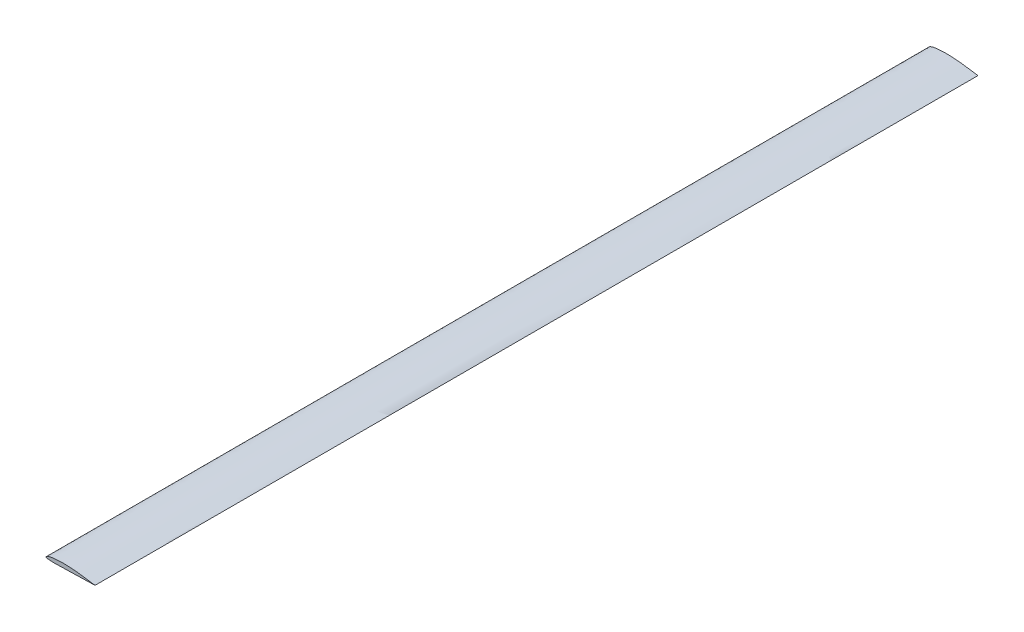
SolidWorks part; units mm, degrees
material "1060 Alloy"
ref_plane "Front Plane" through (0, 0, 0) normal (0, 0, 1) x (1, 0, 0)
ref_plane "Top Plane" through (0, 0, 0) normal (0, 1, 0) x (1, 0, 0)
ref_plane "Right Plane" through (0, 0, 0) normal (1, 0, 0) x (0, 0, -1)
curve "Curve1"
  spline degree 3 poles (99.303, 0.018, 0) (100.1768, -0.0106, 0) (99.3044, 0.0659, 0) (98.6022, 0.1664, 0) (96.9185, 0.3889, 0) (94.883, 0.6998, 0) (92.2676, 1.1097, 0) (89.231, 1.5986, 0) (85.7846, 2.1502, 0) (81.9915, 2.742, 0) (77.8954, 3.3493, 0) (73.5406, 3.9422, 0) (68.9677, 4.4995, 0) (64.218, 5.0097, 0) (59.3372, 5.4645, 0) (54.3778, 5.8636, 0) (49.3943, 6.1992, 0) (44.4376, 6.4503, 0) (39.5569, 6.6096, 0) (34.7991, 6.6775, 0) (30.2086, 6.6419, 0) (25.8275, 6.4985, 0) (21.6951, 6.2592, 0) (17.849, 5.9192, 0) (14.3226, 5.4809, 0) (11.143, 4.9534, 0) (8.3342, 4.3478, 0) (5.9153, 3.6753, 0) (3.9009, 2.9545, 0) (2.2976, 2.2061, 0) (1.1175, 1.4622, 0) (0.4562, 0.8732, 0) (0.18, 0.4789, 0) (0.0816, 0.3044, 0) (0.0209, 0.1477, 0) (-0.0031, 0.0241, 0) (0.0017, -0.0733, 0) (0.0494, -0.1608, 0) (0.1388, -0.2609, 0) (0.2821, -0.3771, 0) (0.6288, -0.5925, 0) (1.401, -0.9072, 0) (2.7562, -1.2563, 0) (4.6749, -1.5755, 0) (7.0779, -1.8364, 0) (9.9483, -2.0308, 0) (13.2624, -2.1587, 0) (16.9912, -2.2213, 0) (21.0993, -2.224, 0) (25.5455, -2.1736, 0) (30.2829, -2.0779, 0) (35.2597, -1.9445, 0) (40.4207, -1.7811, 0) (45.7076, -1.5953, 0) (51.0606, -1.3938, 0) (56.4181, -1.185, 0) (61.7181, -0.9753, 0) (66.898, -0.7732, 0) (71.8957, -0.5848, 0) (76.65, -0.4161, 0) (81.102, -0.2717, 0) (85.1928, -0.157, 0) (88.8721, -0.0729, 0) (92.0755, -0.0183, 0) (94.798, 0.0086, 0) (96.8881, 0.0191, 0) (98.5945, 0.0084, 0) (99.303, 0.018, 0) (100.1768, -0.0106, 0) (99.3044, 0.0659, 0) knots -0.014204 -0.006419 -0.001632 0 0.001631 0.006435 0.014221 0.024766 0.037827 0.053149 0.070474 0.089536 0.110075 0.13186 0.154693 0.178371 0.20268 0.227364 0.252133 0.276728 0.300939 0.324527 0.347267 0.368992 0.389507 0.408628 0.426224 0.442179 0.456396 0.468805 0.479372 0.488086 0.494968 0.500034 0.501036 0.502094 0.502997 0.503513 0.503956 0.504409 0.504955 0.505943 0.50713 0.510998 0.518232 0.527846 0.539809 0.554056 0.57049 0.588974 0.609342 0.631393 0.654894 0.67959 0.705203 0.731447 0.75802 0.78462 0.810936 0.836657 0.861473 0.885081 0.907188 0.927507 0.945765 0.961712 0.975122 0.985796 0.993581 0.998368 1 1.001631 1.006435 1.014221 periodic
sketch "Sketch1" plane through (0, 0, 0) normal (0, 0, 1) x (1, 0, 0)
  spline S0 degree 3 poles (99.303, 0.018) (100.1768, -0.0106) (99.3044, 0.0659) (98.6022, 0.1664) (96.9185, 0.3889) (94.883, 0.6998) (92.2676, 1.1097) (89.231, 1.5986) (85.7846, 2.1502) (81.9915, 2.742) (77.8954, 3.3493) (73.5406, 3.9422) (68.9677, 4.4995) (64.218, 5.0097) (59.3372, 5.4645) (54.3778, 5.8636) (49.3943, 6.1992) (44.4376, 6.4503) (39.5569, 6.6096) (34.7991, 6.6775) (30.2086, 6.6419) (25.8275, 6.4985) (21.6951, 6.2592) (17.849, 5.9192) (14.3226, 5.4809) (11.143, 4.9534) (8.3342, 4.3478) (5.9153, 3.6753) (3.9009, 2.9545) (2.2976, 2.2061) (1.1175, 1.4622) (0.4562, 0.8732) (0.18, 0.4789) (0.0816, 0.3044) (0.0209, 0.1477) (-0.0031, 0.0241) (0.0017, -0.0733) (0.0494, -0.1608) (0.1388, -0.2609) (0.2821, -0.3771) (0.6288, -0.5925) (1.401, -0.9072) (2.7562, -1.2563) (4.6749, -1.5755) (7.0779, -1.8364) (9.9483, -2.0308) (13.2624, -2.1587) (16.9912, -2.2213) (21.0993, -2.224) (25.5455, -2.1736) (30.2829, -2.0779) (35.2597, -1.9445) (40.4207, -1.7811) (45.7076, -1.5953) (51.0606, -1.3938) (56.4181, -1.185) (61.7181, -0.9753) (66.898, -0.7732) (71.8957, -0.5848) (76.65, -0.4161) (81.102, -0.2717) (85.1928, -0.157) (88.8721, -0.0729) (92.0755, -0.0183) (94.798, 0.0086) (96.8881, 0.0191) (98.5945, 0.0084) (99.303, 0.018) (100.1768, -0.0106) (99.3044, 0.0659) knots -0.014204 -0.006419 -0.001632 0 0.001631 0.006435 0.014221 0.024766 0.037827 0.053149 0.070474 0.089536 0.110075 0.13186 0.154693 0.178371 0.20268 0.227364 0.252133 0.276728 0.300939 0.324527 0.347267 0.368992 0.389507 0.408628 0.426224 0.442179 0.456396 0.468805 0.479372 0.488086 0.494968 0.500034 0.501036 0.502094 0.502997 0.503513 0.503956 0.504409 0.504955 0.505943 0.50713 0.510998 0.518232 0.527846 0.539809 0.554056 0.57049 0.588974 0.609342 0.631393 0.654894 0.67959 0.705203 0.731447 0.75802 0.78462 0.810936 0.836657 0.861473 0.885081 0.907188 0.927507 0.945765 0.961712 0.975122 0.985796 0.993581 0.998368 1 1.001631 1.006435 1.014221 only from (100, 0) to (100, 0) construction
  spline S1 degree 3 poles (99.303, 0.018) (100.1768, -0.0106) (99.3044, 0.0659) (98.6022, 0.1664) (96.9185, 0.3889) (94.883, 0.6998) (92.2676, 1.1097) (89.231, 1.5986) (85.7846, 2.1502) (81.9915, 2.742) (77.8954, 3.3493) (73.5406, 3.9422) (68.9677, 4.4995) (64.218, 5.0097) (59.3372, 5.4645) (54.3778, 5.8636) (49.3943, 6.1992) (44.4376, 6.4503) (39.5569, 6.6096) (34.7991, 6.6775) (30.2086, 6.6419) (25.8275, 6.4985) (21.6951, 6.2592) (17.849, 5.9192) (14.3226, 5.4809) (11.143, 4.9534) (8.3342, 4.3478) (5.9153, 3.6753) (3.9009, 2.9545) (2.2976, 2.2061) (1.1175, 1.4622) (0.4562, 0.8732) (0.18, 0.4789) (0.0816, 0.3044) (0.0209, 0.1477) (-0.0031, 0.0241) (0.0017, -0.0733) (0.0494, -0.1608) (0.1388, -0.2609) (0.2821, -0.3771) (0.6288, -0.5925) (1.401, -0.9072) (2.7562, -1.2563) (4.6749, -1.5755) (7.0779, -1.8364) (9.9483, -2.0308) (13.2624, -2.1587) (16.9912, -2.2213) (21.0993, -2.224) (25.5455, -2.1736) (30.2829, -2.0779) (35.2597, -1.9445) (40.4207, -1.7811) (45.7076, -1.5953) (51.0606, -1.3938) (56.4181, -1.185) (61.7181, -0.9753) (66.898, -0.7732) (71.8957, -0.5848) (76.65, -0.4161) (81.102, -0.2717) (85.1928, -0.157) (88.8721, -0.0729) (92.0755, -0.0183) (94.798, 0.0086) (96.8881, 0.0191) (98.5945, 0.0084) (99.303, 0.018) (100.1768, -0.0106) (99.3044, 0.0659) knots -0.014204 -0.006419 -0.001632 0 0.001631 0.006435 0.014221 0.024766 0.037827 0.053149 0.070474 0.089536 0.110075 0.13186 0.154693 0.178371 0.20268 0.227364 0.252133 0.276728 0.300939 0.324527 0.347267 0.368992 0.389507 0.408628 0.426224 0.442179 0.456396 0.468805 0.479372 0.488086 0.494968 0.500034 0.501036 0.502094 0.502997 0.503513 0.503956 0.504409 0.504955 0.505943 0.50713 0.510998 0.518232 0.527846 0.539809 0.554056 0.57049 0.588974 0.609342 0.631393 0.654894 0.67959 0.705203 0.731447 0.75802 0.78462 0.810936 0.836657 0.861473 0.885081 0.907188 0.927507 0.945765 0.961712 0.975122 0.985796 0.993581 0.998368 1 1.001631 1.006435 1.014221 only from (100, 0) to (100, 0)
extrude "Boss-Extrude1" add sketch "Sketch1" along normal blind 1800
ref_plane "Plane1" through (0, 0, 0) normal (0, 1, 0) x (1, 0, 0)
sketch "Sketch2" plane through (0, 0, 0) normal (0, 1, 0) x (1, 0, 0)
  line L0 (49.9999, -1800) -> (49.9999, 0) construction
  line L1 (-0.0002, -1800) -> (100, -1800) construction
  line L2 (100, 0) -> (-0.0002, 0) construction
  line L3 (-0.0002, -900) -> (100, -900) construction
  line L4 (-0.0002, 0) -> (-0.0002, -1800) construction
  line L5 (100, -1800) -> (100, 0) construction
  line L7 (4.9999, -895) -> (94.9999, -895)
  line L8 (4.9999, -895) -> (4.9999, -905)
  line L9 (4.9999, -905) -> (94.9999, -905)
  line L10 (94.9999, -895) -> (94.9999, -905)
  line L11 (4.9999, -895) -> (94.9999, -905) construction
  line L12 (4.9999, -905) -> (94.9999, -895) construction
  point P12 (49.9999, -900)
  dimension "D1" = 10
  dimension "D2" = 90
extrude "Boss-Extrude2" add sketch "Sketch2" against normal blind 5
